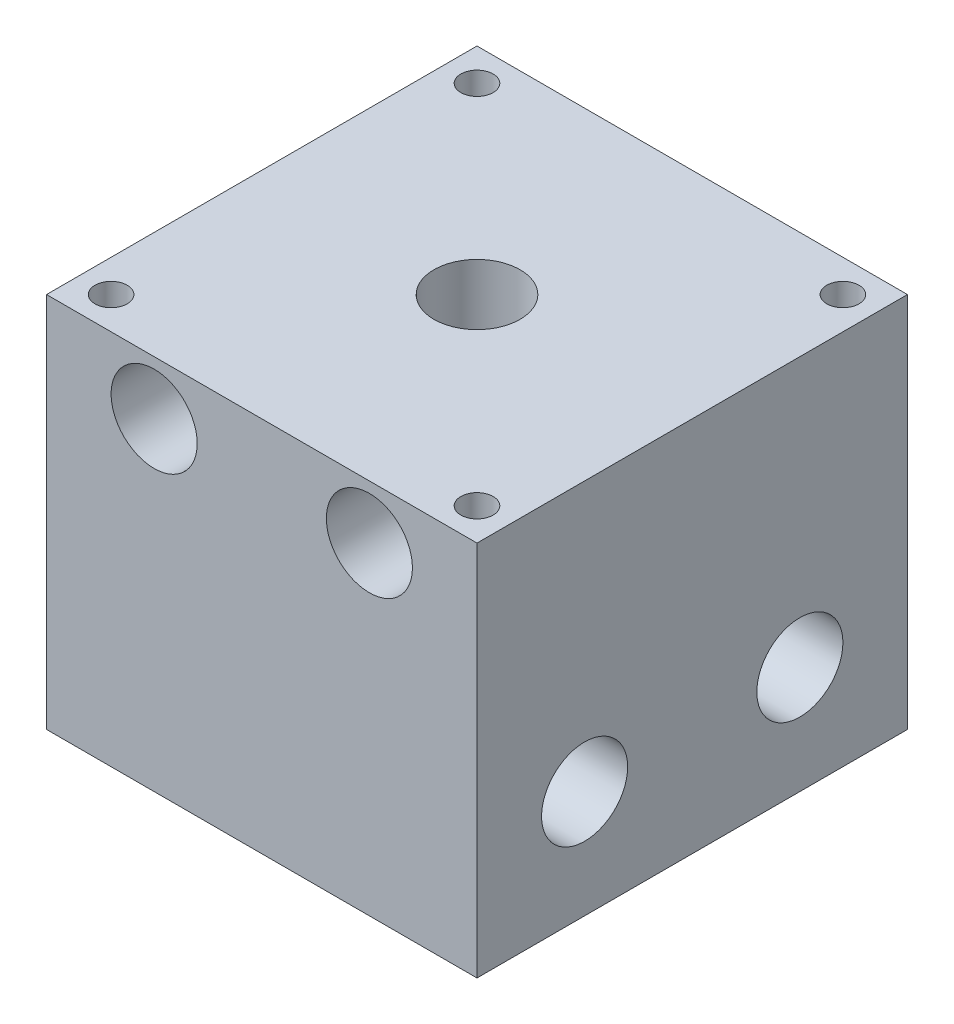
SolidWorks part; units mm, degrees
ref_plane "Front Plane" through (0, 0, 0) normal (0, 0, 1) x (1, 0, 0)
ref_plane "Top Plane" through (0, 0, 0) normal (0, 1, 0) x (1, 0, 0)
ref_plane "Right Plane" through (0, 0, 0) normal (1, 0, 0) x (0, 0, -1)
sketch "Sketch1" plane through (0, 0, 0) normal (0, 1, 0) x (1, 0, 0)
  line L1 (0, 0) -> (40, 0)
  line L2 (0, 0) -> (0, 40)
  line L3 (0, 40) -> (40, 40)
  line L4 (40, 0) -> (40, 40)
  dimension "D1" = 40
  dimension "D2" = 40
extrude "Boss-Extrude1" add sketch "Sketch1" along normal blind 45
sketch "Sketch2" plane through (0, 0, 0) normal (0, 0, 1) x (1, 0, 0)
  line L0 (0, 0) -> (40, 0) construction
  line L1 (0, 45) -> (0, 0) construction
  line L2 (40, 45) -> (40, 0) construction
  circle A0 centre (10, 30) radius 4
  circle A1 centre (30, 30) radius 4
  point P6 (0, 0)
  dimension "D1" = 8
  dimension "D2" = 8
  dimension "D3" = 30
  dimension "D4" = 30
  dimension "D5" = 10
  dimension "D6" = 10
extrude "Cut-Extrude1" cut sketch "Sketch2" against normal blind 45
sketch "Sketch3" plane through (40, 0, 0) normal (1, 0, 0) x (0, 0, -1)
  line L0 (40, 45) -> (40, 0) construction
  line L1 (0, 45) -> (0, 0) construction
  line L2 (0, 0) -> (40, 0) construction
  circle A0 centre (10, 10) radius 4
  circle A1 centre (30, 10) radius 4
  dimension "D1" = 8
  dimension "D2" = 8
  dimension "D3" = 10
  dimension "D4" = 10
  dimension "D5" = 10
  dimension "D6" = 10
extrude "Cut-Extrude2" cut sketch "Sketch3" against normal blind 45
sketch "Sketch4" plane through (0, 45, 0) normal (0, 1, 0) x (1, 0, 0)
  line L0 (40, 0) -> (40, 40) construction
  line L1 (0, 0) -> (40, 0) construction
  line L2 (40, 40) -> (0, 40) construction
  line L3 (0, 40) -> (0, 0) construction
  circle A0 centre (20, 20) radius 4
  circle A1 centre (3, 3) radius 1.5
  circle A2 centre (3, 37) radius 1.5
  circle A3 centre (37, 37) radius 1.5
  circle A4 centre (37, 3) radius 1.5
  dimension "D1" = 8
  dimension "D4" = 3
  dimension "D5" = 3
  dimension "D6" = 3
  dimension "D7" = 3
  dimension "D9" = 3
  dimension "D10" = 3
  dimension "D11" = 3
  dimension "D12" = 3
  dimension "D13" = 3
  dimension "D14" = 3
  dimension "D15" = 3
  dimension "D2" = 20
  dimension "D3" = 20
  dimension "D8" = 3
extrude "Cut-Extrude13" cut sketch "Sketch4" against normal blind 45
sketch "Sketch9" plane through (0, 0, 0) normal (0, 0, 1) x (1, 0, 0)
  line L0 (0, 45) -> (0, 0) construction
  line L1 (40, 45) -> (0, 45)
  line L2 (40, 45) -> (40, 35)
  line L3 (40, 35) -> (0, 35)
  line L4 (0, 45) -> (0, 35)
  dimension "D1" = 10
extrude "Cut-Extrude18" cut sketch "Sketch9" against normal blind 45
